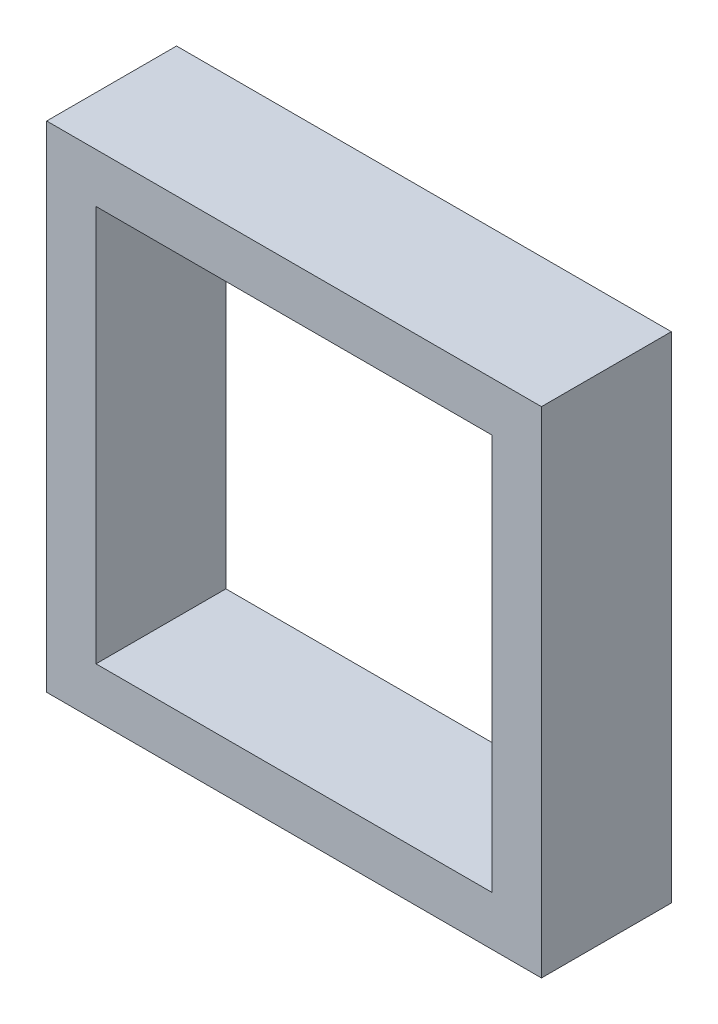
SolidWorks part; units mm, degrees
ref_plane "Plan de face" through (0, 0, 0) normal (0, 0, 1) x (1, 0, 0)
ref_plane "Plan de dessus" through (0, 0, 0) normal (0, 1, 0) x (1, 0, 0)
ref_plane "Plan de droite" through (0, 0, 0) normal (1, 0, 0) x (0, 0, -1)
sketch "Esquisse1" plane through (0, 0, 0) normal (0, 0, 1) x (1, 0, 0)
  line L1 (-19.05, -19.05) -> (19.05, -19.05)
  line L2 (-19.05, -19.05) -> (-19.05, 19.05)
  line L3 (-19.05, 19.05) -> (19.05, 19.05)
  line L4 (19.05, -19.05) -> (19.05, 19.05)
  line L5 (-19.05, -19.05) -> (19.05, 19.05) construction
  line L6 (-19.05, 19.05) -> (19.05, -19.05) construction
  line L7 (-15.25, -15.25) -> (15.25, -15.25)
  line L8 (-15.25, -15.25) -> (-15.25, 15.25)
  line L9 (-15.25, 15.25) -> (15.25, 15.25)
  line L10 (15.25, -15.25) -> (15.25, 15.25)
  line L11 (-15.25, -15.25) -> (15.25, 15.25) construction
  line L12 (-15.25, 15.25) -> (15.25, -15.25) construction
  point P0 (0, 0)
  point P6 (0, 0)
  dimension "D1" = 30.5
  dimension "D2" = 38.1
  dimension "D3" = 38.1
extrude "Boss.-Extru.1" add sketch "Esquisse1" along normal blind 10
